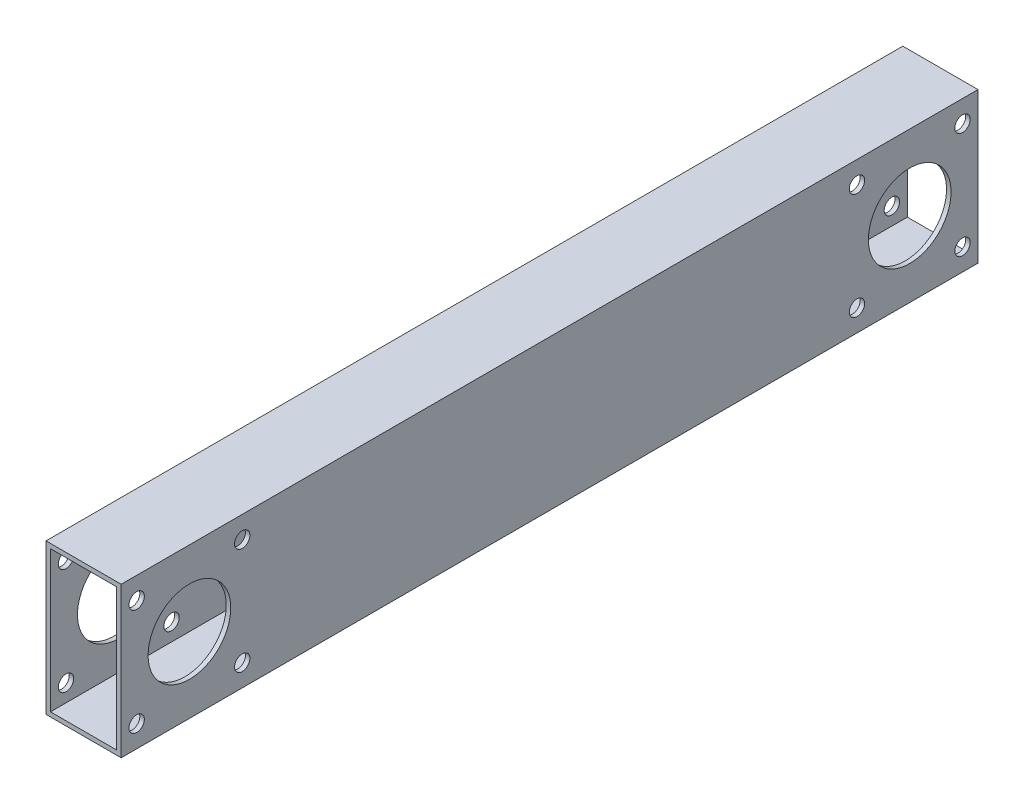
SolidWorks part; units mm, degrees
ref_plane "Front Plane" through (0, 0, 0) normal (0, 0, 1) x (1, 0, 0)
ref_plane "Top Plane" through (0, 0, 0) normal (0, 1, 0) x (1, 0, 0)
ref_plane "Right Plane" through (0, 0, 0) normal (1, 0, 0) x (0, 0, -1)
sketch "Sketch1" plane through (0, 0, 0) normal (0, 0, 1) x (1, 0, 0)
  line L0 (0, 0) -> (50, 0)
  line L1 (50, 0) -> (50, 100)
  line L2 (50, 100) -> (0, 100)
  line L3 (0, 100) -> (0, 0)
  line L4 (47, 97) -> (3, 97)
  line L5 (3, 97) -> (3, 3)
  line L6 (3, 3) -> (47, 3)
  line L7 (47, 3) -> (47, 97)
  dimension "D1" = 100
  dimension "D2" = 50
  dimension "D3" = 3
extrude "Boss-Extrude1" add sketch "Sketch1" along normal blind 570
sketch "Sketch2" plane through (0, 0, 0) normal (-1, 0, 0) x (0, 0, 1)
  line L0 (0, 50) -> (570, 50) construction
  line L1 (0, 100) -> (0, 0) construction
  line L2 (570, 100) -> (570, 0) construction
  line L3 (285, 100) -> (285, -73.1912) construction
  line L4 (570, 100) -> (0, 100) construction
  circle A0 centre (45.4135, 50) radius 27.5
  circle A1 centre (524.5865, 50) radius 27.5
  dimension "D1" = 55
extrude "Cut-Extrude1" cut sketch "Sketch2" against normal blind 570
sketch "Sketch3" plane through (0, 0, 0) normal (-1, 0, 0) x (0, 0, 1)
  line L0 (0, 50) -> (641.6285, 50) construction
  line L1 (0, 100) -> (0, 0) construction
  line L2 (45.4135, 50) -> (45.4135, 137.7026) construction
  line L3 (285, 100) -> (285, -93.3806) construction
  line L4 (570, 100) -> (0, 100) construction
  line L5 (524.5865, 50) -> (524.5865, 137.7026) construction
  circle A0 centre (10.2992, 85.4597) radius 5.1152
  circle A1 centre (80.5279, 85.4597) radius 5.1152
  circle A2 centre (80.5279, 14.5403) radius 5.1152
  circle A3 centre (10.2992, 14.5403) radius 5.1152
  circle A4 centre (80.5279, 14.5403) radius 5.1152
  circle A5 centre (10.2992, 14.5403) radius 5.1152
  circle A6 centre (10.2992, 85.4597) radius 5.1152
  circle A7 centre (80.5279, 85.4597) radius 5.1152
  circle A8 centre (489.4721, 85.4597) radius 5.1152
  circle A9 centre (559.7008, 85.4597) radius 5.1152
  circle A10 centre (559.7008, 14.5403) radius 5.1152
  circle A11 centre (489.4721, 14.5403) radius 5.1152
  circle A12 centre (559.7008, 14.5403) radius 5.1152
  circle A13 centre (489.4721, 14.5403) radius 5.1152
  circle A14 centre (489.4721, 85.4597) radius 5.1152
  circle A15 centre (559.7008, 85.4597) radius 5.1152
  point P37 (0, 0)
extrude "Cut-Extrude2" cut sketch "Sketch3" against normal blind 570 contours A1 | A3 | A2 | A9 | A8 | A11 | A10 | A0
